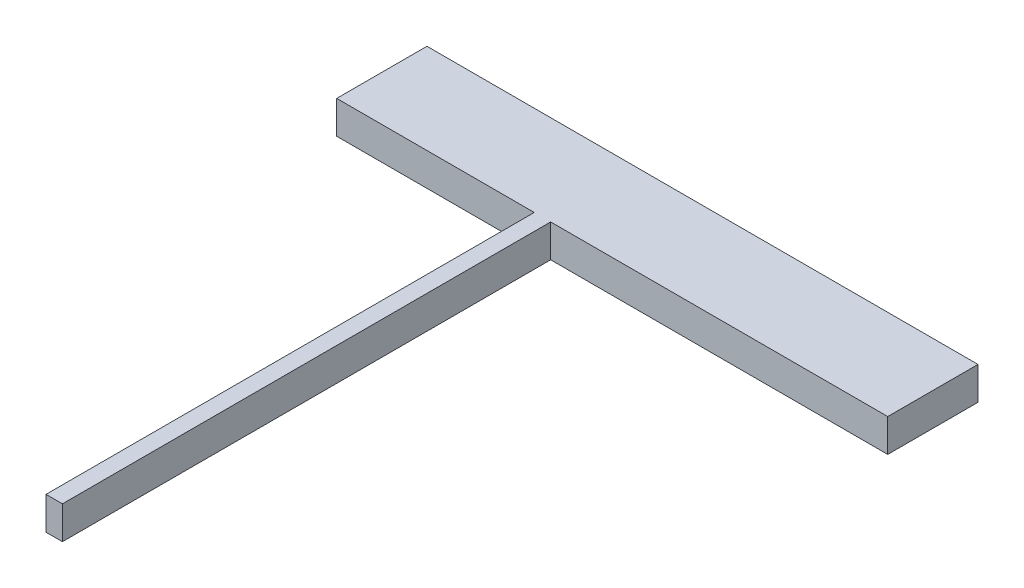
SolidWorks part; units mm, degrees
ref_plane "前视基准面" through (0, 0, 0) normal (0, 0, 1) x (1, 0, 0)
ref_plane "上视基准面" through (0, 0, 0) normal (0, 1, 0) x (1, 0, 0)
ref_plane "右视基准面" through (0, 0, 0) normal (1, 0, 0) x (0, 0, -1)
other "Configuration Table"
sketch "草图1" plane through (0, 0, 0) normal (0, 1, 0) x (1, 0, 0)
  line L1 (-67.15, 11) -> (67.15, 11)
  line L2 (-67.15, 11) -> (-67.15, -11)
  line L3 (-67.15, -11) -> (67.15, -11)
  line L4 (67.15, 11) -> (67.15, -11)
  line L5 (-67.15, 11) -> (67.15, -11) construction
  line L6 (-67.15, -11) -> (67.15, 11) construction
  point P0 (0, 0)
  dimension "D1" = 134.3
  dimension "D2" = 22
extrude "凸台-拉伸1" add sketch "草图1" along normal blind 8
sketch "草图2" plane through (0, 0, 0) normal (0, 0, 1) x (1, 0, 0)
  line L0 (-67.15, 0) -> (67.15, 0) construction
  line L1 (-15, 0) -> (-15, 8)
  line L2 (-67.15, 8) -> (67.15, 8) construction
  line L3 (-15, 8) -> (-19, 8)
  line L4 (-19, 8) -> (-19, 0)
  line L5 (-19, 0) -> (-15, 0)
  point P0 (-17, 0)
  point P1 (-15, 0)
  point P5 (-19, 0)
  dimension "D1" = 17
  dimension "D2" = 15
  dimension "D3" = 19
extrude "凸台-拉伸2" add sketch "草图2" along normal blind 130
